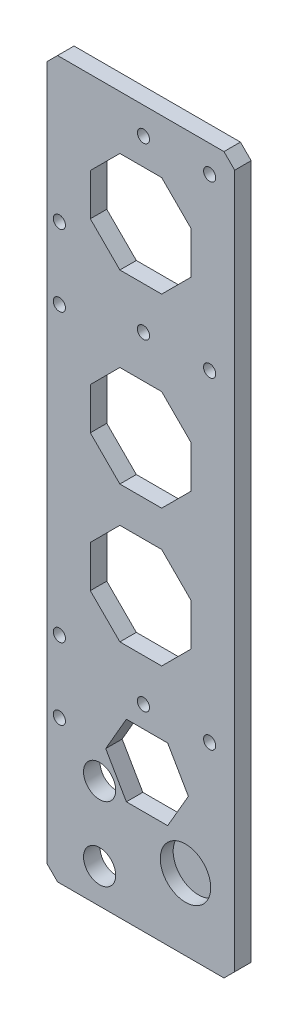
SolidWorks part; units mm, degrees
material "PA Tipo 6"
ref_plane "Alzado" through (0, 0, 0) normal (1, 0, 0) x (0, 1, 0)
ref_plane "Planta" through (0, 0, 0) normal (0, 0, 1) x (0, 1, 0)
ref_plane "Vista lateral" through (0, 0, 0) normal (0, 1, 0) x (-1, 0, 0)
sketch "Croquis1" plane through (0, 0, 0) normal (0, 0, 1) x (0, 1, 0)
  line L1 (-100, 26.25) -> (100, 26.25)
  line L2 (-100, 26.25) -> (-100, -26.25)
  line L3 (-100, -26.25) -> (100, -26.25)
  line L4 (100, 26.25) -> (100, -26.25)
  line L5 (-100, 26.25) -> (100, -26.25) construction
  line L6 (-100, -26.25) -> (100, 26.25) construction
  point P0 (0, 0)
  dimension "D1" = 52.5
  dimension "D2" = 200
extrude "Saliente-Extruir1" add sketch "Croquis1" along normal blind 4.6
sketch "Croquis2" plane through (0, 0, 4.6) normal (0, 0, 1) x (1, 0, 0)
  line L0 (12.5, 0) -> (12.5, -180.2551) construction
  line L1 (-26.25, -100) -> (26.25, -100) construction
  line L2 (12.5, -80) -> (18.7, -80) construction
  line L5 (12.5, 0) -> (103.0782, 0) construction
  circle A4 centre (12.5, -80) radius 7.05
  dimension "D1" = 14.1
  dimension "D3" = 20
  dimension "D4" = 12.5
extrude "Cortar-Extruir1" cut sketch "Croquis2" against normal blind 3.6
sketch "Croquis4" plane through (0, 0, 0) normal (0, 0, -1) x (1, 0, 0)
  line L0 (0, 0) -> (-35.9176, 0) construction
  point P0 (19.25, -45)
  point P3 (19.25, 45)
  point P5 (0.75, 45)
  point P9 (0.75, -45)
  dimension "D1" = 45
  dimension "D2" = 18.5
  dimension "D3" = 0.75
hole_wizard "Taladro de margen para M31" positions "Croquis4" profile "Croquis5" hole size "M3" standard "Ansi Metric" end condition through all
sketch "Croquis5" plane through (19.25, 45, 0) normal (1, 0, 0) x (0, 1, 0)
  line L0 (0, 0) -> (0, 4.6)
  line L1 (0, 4.6) -> (1.7, 4.6)
  line L2 (1.7, 4.6) -> (1.7, 0)
  line L5 (1.7, 0) -> (0, 0)
  line L11 (0, -6.35) -> (0, 107.95) construction
  dimension "Diámetro de taladro hasta el siguiente" = 3.4
  dimension "Profundidad de taladro hasta el siguiente" = 4.6
chamfer "Chaflán1" distance 3 angle 45 4 edges at (-26.25, 100, 2.3) (26.25, 100, 2.3) (26.25, -100, 2.3) (-26.25, -100, 2.3)
sketch "Croquis6" plane through (0, 0, 4.6) normal (0, 0, 1) x (1, 0, 0)
  line L0 (-26.25, 0) -> (26.25, 0) construction
  line L1 (-26.25, 97) -> (-26.25, -97) construction
  line L2 (26.25, -97) -> (26.25, 97) construction
  point P0 (-22.75, -60)
  point P1 (-22.75, -40)
  point P3 (-22.75, 40)
  point P5 (-22.75, 60)
  dimension "D1" = 3.5
  dimension "D2" = 40
  dimension "D3" = 20
hole_wizard "Taladro de margen para M32" positions "Croquis6" profile "Croquis7" hole size "M3" standard "Ansi Metric" end condition through all
sketch "Croquis7" plane through (-22.75, -60, 4.6) normal (1, 0, 0) x (0, -1, 0)
  line L0 (0, 0) -> (0, 4.6)
  line L1 (0, 4.6) -> (1.7, 4.6)
  line L2 (1.7, 4.6) -> (1.7, 0)
  line L5 (1.7, 0) -> (0, 0)
  line L11 (0, -6.35) -> (0, 107.95) construction
  dimension "Diámetro de taladro hasta el siguiente" = 3.4
  dimension "Profundidad de taladro hasta el siguiente" = 4.6
sketch "Croquis8" plane through (0, 0, 4.6) normal (0, 0, 1) x (1, 0, 0)
  line L0 (26.25, 0) -> (-26.25, 0) construction
  line L1 (26.25, -97) -> (26.25, 97) construction
  line L2 (-26.25, 97) -> (-26.25, -97) construction
  line L3 (0.75, 45) -> (0.75, 0) construction
  line L20 (-5.8404, 33.2) -> (5.8404, 33.2)
  line L37 (5.8404, -33.2) -> (14.1, -24.9404)
  line L38 (13.297, -61) -> (7.5235, -51)
  line L39 (7.5235, -51) -> (-4.0235, -51)
  line L40 (-4.0235, -51) -> (-9.797, -61)
  line L41 (-9.797, -61) -> (-4.0235, -71)
  line L42 (-4.0235, -71) -> (7.5235, -71)
  line L43 (7.5235, -71) -> (13.297, -61)
  line L44 (14.1, -24.9404) -> (14.1, -13.2596)
  line L45 (14.1, -13.2596) -> (5.8404, -5)
  line L46 (5.8404, -5) -> (-5.8404, -5)
  line L47 (-5.8404, -5) -> (-14.1, -13.2596)
  line L48 (-14.1, -13.2596) -> (-14.1, -24.9404)
  line L49 (-14.1, -24.9404) -> (-5.8404, -33.2)
  line L50 (-5.8404, -33.2) -> (5.8404, -33.2)
  line L51 (-14.1, 24.9404) -> (-5.8404, 33.2)
  line L52 (-14.1, 13.2596) -> (-14.1, 24.9404)
  line L53 (-5.8404, 5) -> (-14.1, 13.2596)
  line L54 (5.8404, 5) -> (-5.8404, 5)
  line L55 (14.1, 13.2596) -> (5.8404, 5)
  line L56 (14.1, 24.9404) -> (14.1, 13.2596)
  line L57 (5.8404, 33.2) -> (14.1, 24.9404)
  line L58 (0.75, 45) -> (54.4766, 45) construction
  line L59 (5.8404, 56.8) -> (14.1, 65.0596)
  line L60 (14.1, 65.0596) -> (14.1, 76.7404)
  line L61 (14.1, 76.7404) -> (5.8404, 85)
  line L62 (5.8404, 85) -> (-5.8404, 85)
  line L63 (-5.8404, 85) -> (-14.1, 76.7404)
  line L64 (-14.1, 76.7404) -> (-14.1, 65.0596)
  line L65 (-14.1, 65.0596) -> (-5.8404, 56.8)
  line L66 (-5.8404, 56.8) -> (5.8404, 56.8)
  circle A0 centre (0, -19.1) radius 14.1 construction
  circle A5 centre (1.75, -61) radius 10 construction
  circle A7 centre (0, 19.1) radius 14.1 construction
  circle A8 centre (0, 70.9) radius 14.1 construction
  dimension "D4" = 61
  dimension "D6" = 28.2
  dimension "D5" = 20
  dimension "D1" = 5
  dimension "D2" = 0.75
  dimension "D3" = 1.75
extrude "Cortar-Extruir2" cut sketch "Croquis8" against normal through all
sketch "Croquis9" plane through (0, 0, 4.6) normal (0, 0, 1) x (1, 0, 0)
  line L0 (0, 100) -> (0, 71.7513) construction
  line L1 (23.25, 100) -> (-23.25, 100) construction
  point P0 (0.75, 92.5)
  point P6 (19.25, 92.5)
  dimension "D1" = 18.5
  dimension "D2" = 7.5
  dimension "D3" = 0.75
hole_wizard "Taladro de margen para M33" positions "Croquis9" profile "Croquis10" hole size "M3" standard "Ansi Metric" end condition through all
sketch "Croquis10" plane through (0.75, 92.5, 4.6) normal (1, 0, 0) x (0, -1, 0)
  line L0 (0, 0) -> (0, 4.6)
  line L1 (0, 4.6) -> (1.7, 4.6)
  line L2 (1.7, 4.6) -> (1.7, 0)
  line L5 (1.7, 0) -> (0, 0)
  line L11 (0, -6.35) -> (0, 107.95) construction
  dimension "Diámetro de taladro hasta el siguiente" = 3.4
  dimension "Profundidad de taladro hasta el siguiente" = 4.6
sketch "Croquis11" plane through (0, 0, 0) normal (0, 0, -1) x (1, 0, 0)
  circle A0 centre (-11.5, 69.7) radius 2 construction
  circle A1 centre (-11.5, 90.3) radius 2 construction
  point P7 (-11.5, 90.3)
  point P8 (-11.5, 69.7)
hole_wizard "Taladro de margen para M81" positions "Croquis11" profile "Croquis12" hole size "M8" standard "Ansi Metric" end condition through all
sketch "Croquis12" plane through (-11.5, -69.7, 0) normal (1, 0, 0) x (0, 1, 0)
  line L0 (0, 0) -> (0, 4.6)
  line L1 (0, 4.6) -> (4.5, 4.6)
  line L2 (4.5, 4.6) -> (4.5, 0)
  line L5 (4.5, 0) -> (0, 0)
  line L11 (0, -6.35) -> (0, 107.95) construction
  dimension "Diámetro de taladro hasta el siguiente" = 9
  dimension "Profundidad de taladro hasta el siguiente" = 4.6
